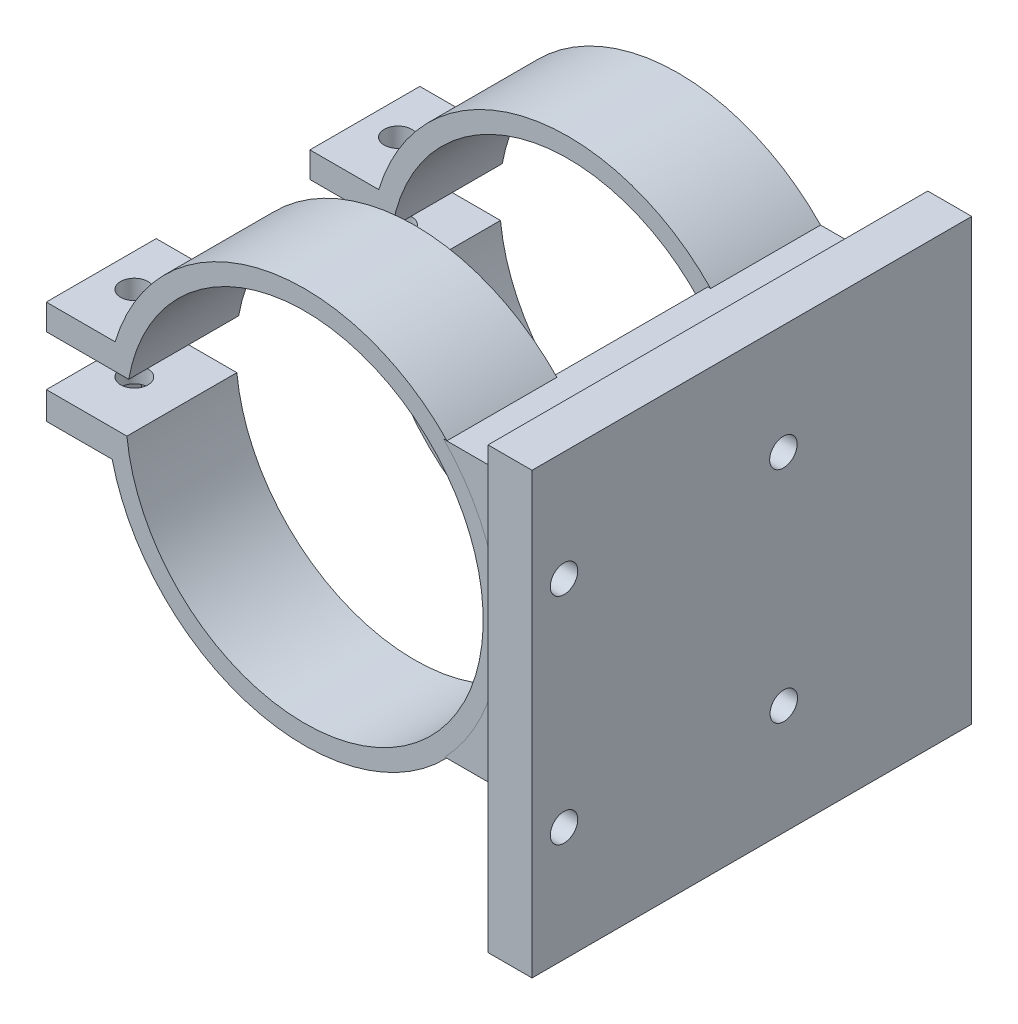
SolidWorks part; units mm, degrees
ref_plane "Plan de face" through (0, 0, 0) normal (0, 0, 1) x (1, 0, 0)
ref_plane "Plan de dessus" through (0, 0, 0) normal (0, 1, 0) x (1, 0, 0)
ref_plane "Plan de droite" through (0, 0, 0) normal (1, 0, 0) x (0, 0, -1)
sketch "Esquisse1" plane through (0, 0, 0) normal (0, 0, 1) x (1, 0, 0)
  line L0 (-71.2738, 9.6549) -> (-56.6225, 9.6549)
  line L1 (-58.7697, 23.4402) -> (-71.2947, 23.4402)
  line L3 (-56.2947, 18.7659) -> (-71.2947, 18.7659)
  line L4 (-71.2947, 23.4402) -> (-71.2947, 18.7659)
  line L5 (-71.2738, 9.6549) -> (-71.2738, 4.6549)
  line L6 (-71.2738, 4.6549) -> (-59.3073, 4.6549)
  arc A0 (-56.6225, 9.6549) -> (-56.2947, 18.7659) centre (-24.3007, 13.0535) ccw
  arc A3 (-59.3073, 4.6549) -> (-58.7697, 23.4402) centre (-24.3007, 13.0535) ccw
extrude "Boss.-Extru.2" add sketch "Esquisse1" along normal blind 20
sketch "Esquisse3" plane through (11.5088, 4.6549, -20.7568) normal (0, -1, 0) x (-1, 0, 0)
  circle A0 centre (76.7831, -30.7568) radius 2.5
extrude "Boss.-Extru.4" add sketch "Esquisse3" along normal blind 2.2401 and the other way blind 20 separate body
sketch "Esquisse8" plane through (38.1661, 0, 0) normal (0, 1, 0) x (1, 0, 0)
  line L1 (-101.4753, -13.4216) -> (-99.5228, -9.9304)
  line L2 (-99.5228, -9.9304) -> (-101.5701, -6.494)
  line L3 (-101.5701, -6.494) -> (-105.5697, -6.5488)
  line L4 (-105.5697, -6.5488) -> (-107.5221, -10.0399)
  line L5 (-107.5221, -10.0399) -> (-105.4749, -13.4763)
  line L6 (-105.4749, -13.4763) -> (-101.4753, -13.4216)
  circle A0 centre (-103.5225, -9.9852) radius 3.4641 construction
extrude "Boss.-Extru.7" add sketch "Esquisse8" along normal blind 6.805 and the other way blind 0.2 separate body
combine bodies "Combiner2" operation type subtract main body 102 bodies to subtract 104 107
move or copy body "Corps-Déplacer/Copier2" bodies to move or copy 109 copy yes number of copies 1 translate (0, 0, 72.965)
sketch "Esquisse13" plane through (0, 0, 0) normal (0, 0, 1) x (1, 0, 0)
  line L1 (22.0413, 59.1588) -> (30.0413, 59.1588)
  line L2 (22.0413, 59.1588) -> (22.0413, -20.8412)
  line L3 (22.0413, -20.8412) -> (30.0413, -20.8412)
  line L4 (30.0413, 59.1588) -> (30.0413, -20.8412)
extrude "Boss.-Extru.9" add sketch "Esquisse13" along normal blind 80 separate body
move or copy body "Corps-Déplacer/Copier3" bodies to move or copy 112 copy no translate (0, 0, -25)
sketch "Esquisse16" plane through (0, 0, 0) normal (1, 0, 0) x (0, 0, -1)
  line L0 (-80, 59.1588) -> (0, 59.1588) construction
  circle A0 centre (-34.2627, 39.1588) radius 2.5
  circle A1 centre (-34.1956, -0.8412) radius 2.5
  circle A2 centre (-74.1764, 0) radius 2.5
  circle A3 centre (-74.1764, 39.1588) radius 2.5
  dimension "D1" = 40
  dimension "D2" = 20
extrude "Boss.-Extru.11" add sketch "Esquisse16" along normal blind 40 and the other way blind 3.5598 separate body
combine bodies "Combiner3" operation type subtract main body 113 bodies to subtract 119 116 118 117
sketch "Esquisse17" plane through (0, 0, 0) normal (0, 0, 1) x (1, 0, 0)
  line L1 (21.2596, 38.0415) -> (1.0983, 38.0415)
  line L2 (21.2596, 38.0415) -> (21.2596, -11.9585)
  line L3 (21.2596, -11.9585) -> (1.2596, -11.9585)
  line L4 (1.0983, 38.0415) -> (1.0983, 37.9898)
  arc A1 (1.2596, -11.9585) -> (1.0983, 37.9898) centre (-24.7494, 12.9319) ccw
extrude "Boss.-Extru.12" add sketch "Esquisse17" along normal blind 68
move or copy body "Corps-Déplacer/Copier4" bodies to move or copy 120 copy no translate (0, -10, 0)
move or copy body "Corps-Déplacer/Copier5" bodies to move or copy 122 copy no translate (0, 5, 0)
move or copy body "Corps-Déplacer/Copier6" bodies to move or copy 123 copy no translate (0, -1, 0)
sketch "Esquisse19" plane through (0, 0, 0) normal (1, 0, 0) x (0, 0, -1)
  circle A0 centre (-34.1956, 32.5329) radius 5.2143
  circle A1 centre (-34.1956, -6.8412) radius 5
move or copy body "Corps-Déplacer/Copier7" bodies to move or copy 124 copy no translate (57.5992, 0, 0)
move or copy body "Corps-Déplacer/Copier8" bodies to move or copy 121 copy no translate (-92, 0, 0)
extrude "Boss.-Extru.15" add sketch "Esquisse19" along normal blind 21.55 separate body contours A0 | A1
move or copy body "Corps-Déplacer/Copier9" bodies to move or copy 128 copy no translate (91.5247, 0, 0)
combine bodies "Combiner6" operation type subtract main body 131 bodies to subtract 129 130
move or copy body "Corps-Déplacer/Copier12" bodies to move or copy 127 copy no translate (-59, 0, 0)
combine bodies "Combiner7" operation type add bodies to combine 137 135
